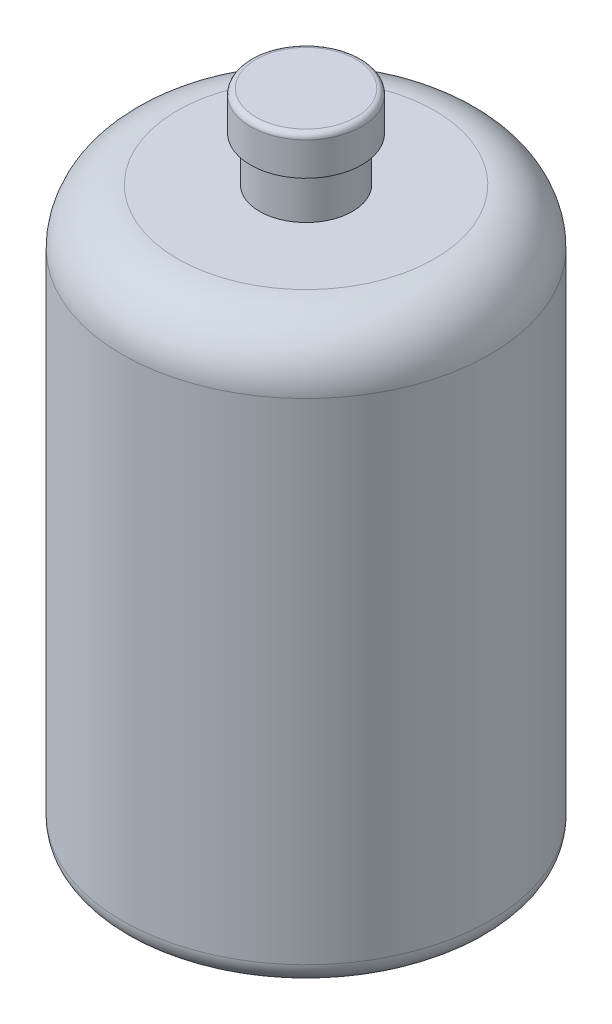
SolidWorks part; units mm, degrees
ref_plane "Front Plane" through (0, 0, 0) normal (0, 0, 1) x (1, 0, 0)
ref_plane "Top Plane" through (0, 0, 0) normal (0, 1, 0) x (1, 0, 0)
ref_plane "Right Plane" through (0, 0, 0) normal (1, 0, 0) x (0, 0, -1)
sketch "Sketch1" plane through (0, 0, 0) normal (0, 1, 0) x (1, 0, 0)
  circle A0 centre (0, 0) radius 33.25
extrude "Boss-Extrude1" add sketch "Sketch1" along normal blind 102.7
sketch "Sketch2" plane through (0, 102.7, 0) normal (0, 1, 0) x (1, 0, 0)
  circle A0 centre (0, 0) radius 10.05
extrude "Boss-Extrude2" add sketch "Sketch2" along normal blind 15.1
fillet "Fillet1" radius 4 1 edges at (0, 0, 33.25)
fillet "Fillet2" radius 10 1 edges at (0, 102.7, 33.25)
fillet "Fillet3" radius 1 1 edges at (0, 117.8, 10.05)
sketch "Sketch4" plane through (0, 102.7, 0) normal (0, 1, 0) x (1, 0, 0)
  circle A0 centre (0, 0) radius 10.05
  circle A1 centre (0, 0) radius 8.4
extrude "Cut-Extrude1" cut sketch "Sketch4" along normal blind 8.1
